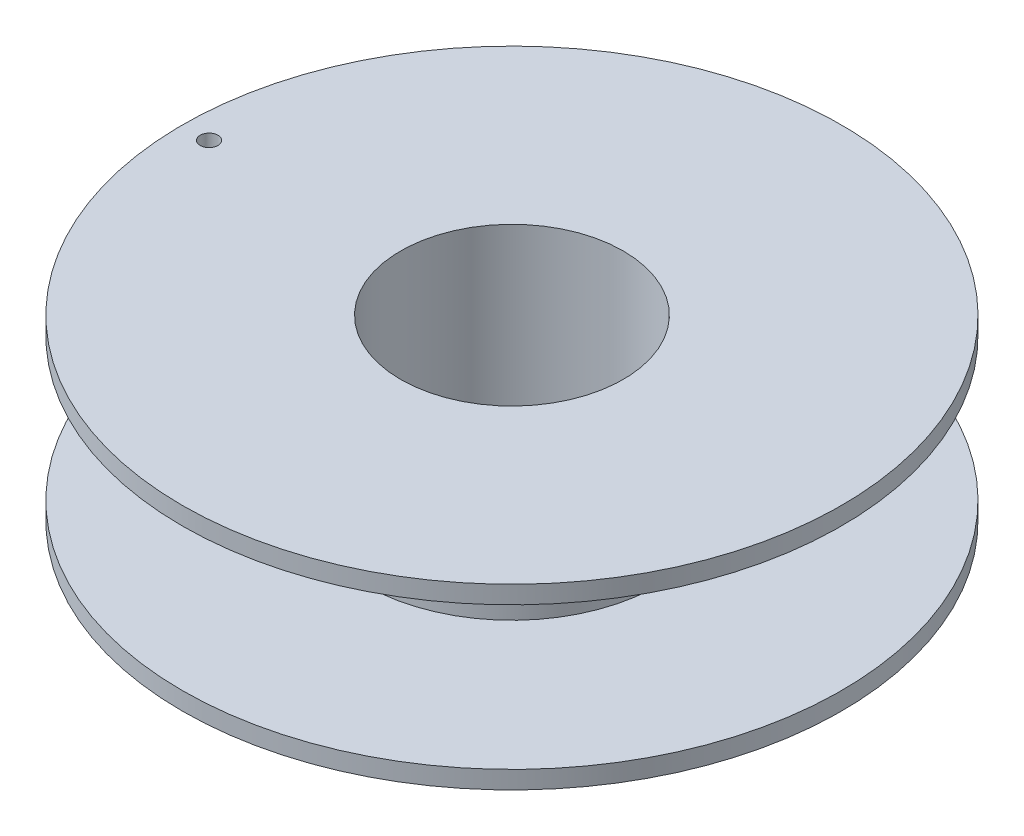
SolidWorks part; units mm, degrees
ref_plane "前视基准面" through (0, 0, 0) normal (0, 0, 1) x (1, 0, 0)
ref_plane "上视基准面" through (0, 0, 0) normal (0, 1, 0) x (1, 0, 0)
ref_plane "右视基准面" through (0, 0, 0) normal (1, 0, 0) x (0, 0, -1)
other "Configuration Table"
sketch "草图2" plane through (0, 0, 0) normal (0, 1, 0) x (1, 0, 0)
  circle A0 centre (0, 0) radius 6.25
  circle A1 centre (0, 0) radius 6.75
  dimension "D1" = 12.5
  dimension "D2" = 0.5
extrude "凸台-拉伸1" add sketch "草图2" along normal mid plane 10
sketch "草图3" plane through (0, 0, 0) normal (0, 1, 0) x (1, 0, 0)
  circle A0 centre (0, 0) radius 6.75
  circle A1 centre (0, 0) radius 18.5
  dimension "D1" = 37
extrude "凸台-拉伸4" add sketch "草图3" along normal mid plane 10
sketch "草图6" plane through (0, 0, 0) normal (0, 1, 0) x (1, 0, 0)
  circle A0 centre (0, 0) radius 6.25
  circle A1 centre (0, 0) radius 8.25
  circle A2 centre (0, 0) radius 18.5
  dimension "D1" = 2
extrude "切除-拉伸3" cut sketch "草图6" against normal mid plane 8 contours A2 A1
sketch "草图7" plane through (0, 0, 0) normal (1, 0, 0) x (0, 0, -1)
  line L0 (0, -4) -> (0, -3.25)
  line L1 (18.5, -4) -> (-18.5, -4) construction
  circle A0 centre (0, -3.25) radius 0.5
  dimension "D1" = 1
  dimension "D2" = 0.75
extrude "切除-拉伸4" cut sketch "草图7" against normal through all
sketch "草图8" plane through (0, 5, 0) normal (0, 1, 0) x (1, 0, 0)
  circle A0 centre (-17, 0) radius 0.5
  circle A1 centre (0, 0) radius 18.5 construction
  dimension "D1" = 1
  dimension "D2" = 17
extrude "切除-拉伸5" cut sketch "草图8" against normal up to next
